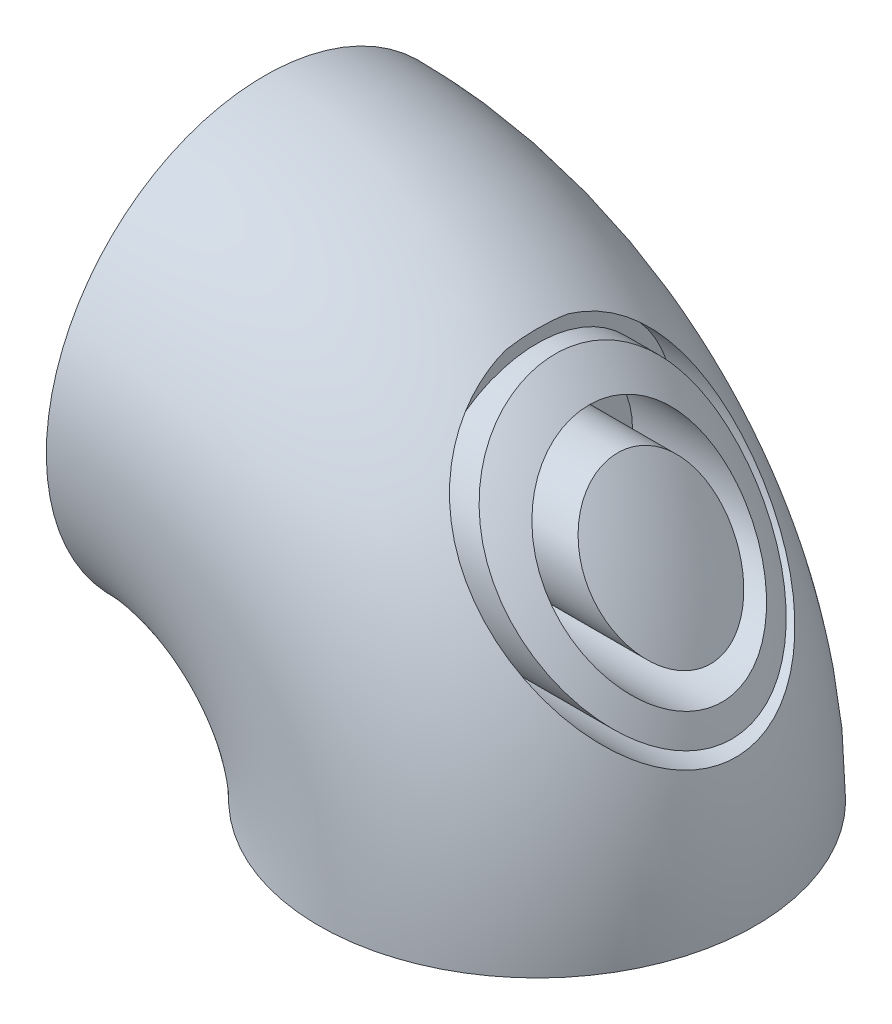
SolidWorks part; units mm, degrees
material "ABS"
ref_plane "Front Plane" through (0, 0, 0) normal (0, 0, 1) x (1, 0, 0)
ref_plane "Top Plane" through (0, 0, 0) normal (0, 1, 0) x (1, 0, 0)
ref_plane "Right Plane" through (0, 0, 0) normal (1, 0, 0) x (0, 0, -1)
sketch "Sketch1" plane through (0, 0, 0) normal (0, 0, 1) x (1, 0, 0)
  arc A0 (0, 0) -> (-100, 100) centre (-100, 0) ccw
sweep "Sweep2" add path "Sketch1" circular profile diameter 160 parameters "D3"=160
sketch "Sketch11" plane through (0, 0, 0) normal (0, -1, 0) x (1, 0, 0)
  circle A0 centre (0, 0) radius 25
extrude "Cut-Extrude1" cut sketch "Sketch11" against normal blind 30
sketch "Sketch12" plane through (-100, 0, 0) normal (-1, 0, 0) x (0, 0, 1)
  circle A0 centre (0, 100) radius 25
extrude "Boss-Extrude1" add sketch "Sketch12" along normal blind 30
sketch "Sketch13" plane through (0, 0, 0) normal (1, 0, 0) x (0, 0, -1)
  line L0 (0, 0) -> (0, 100)
  line L1 (-80, 0) -> (80, 0) construction
  circle A0 centre (0, 100) radius 25
  circle A1 centre (0, 100) radius 35
  circle A2 centre (0, 100) radius 50
  circle A3 centre (0, 100) radius 45
extrude "Cut-Extrude2" cut sketch "Sketch13" along normal through all
